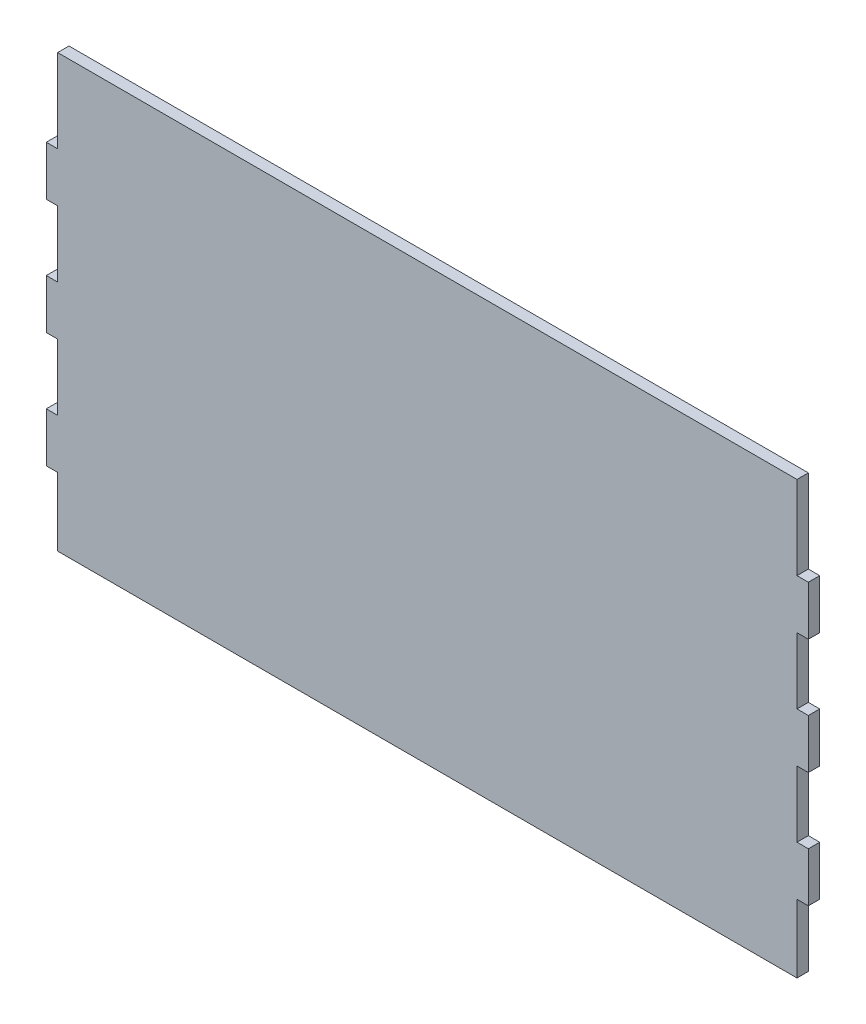
SolidWorks part; units mm, degrees
ref_plane "Front Plane" through (0, 0, 0) normal (0, 0, 1) x (1, 0, 0)
ref_plane "Top Plane" through (0, 0, 0) normal (0, 1, 0) x (1, 0, 0)
ref_plane "Right Plane" through (0, 0, 0) normal (1, 0, 0) x (0, 0, -1)
sketch "Croquis1" plane through (0, 0, 0) normal (0, 0, 1) x (1, 0, 0)
  line L1 (-100.6, 55) -> (100.6, 55)
  line L2 (-100.6, 55) -> (-100.6, -55)
  line L3 (-100.6, -55) -> (100.6, -55)
  line L4 (100.6, 55) -> (100.6, -55)
  line L5 (-100.6, 55) -> (100.6, -55) construction
  line L6 (-100.6, -55) -> (100.6, 55) construction
  point P0 (0, 0)
  dimension "D1" = 201.2
  dimension "D2" = 110
extrude "Saliente-Extruir1" add sketch "Croquis1" along normal blind 3
sketch "Croquis2" plane through (0, 0, 3) normal (0, 0, 1) x (1, 0, 0)
  line L0 (-100.6, 55) -> (-100.6, -55) construction
  line L1 (-100.6, 37) -> (-97.6, 37)
  line L2 (-100.6, 37) -> (-100.6, 23.9518)
  line L3 (-100.6, 23.9518) -> (-97.6, 23.9518)
  line L6 (-100.6, 6.5241) -> (-100.6, -6.5241)
  line L8 (-100.6, 6.5241) -> (-97.6, 6.5241)
  line L10 (-100.6, -6.5241) -> (-97.6, -6.5241)
  line L11 (-100.6, -23.9518) -> (-100.6, -37)
  line L12 (-100.6, -23.9518) -> (-97.6, -23.9518)
  line L14 (-100.6, -37) -> (-97.6, -37)
  line L15 (-100.6, -55) -> (100.6, -55) construction
  line L16 (100.6, 55) -> (-100.6, 55) construction
  line L17 (0, -55) -> (0, 55) construction
  line L18 (100.6, -23.9518) -> (97.6, -23.9518)
  line L19 (-97.6, -52) -> (97.6, -52)
  line L20 (97.6, -52) -> (97.6, 52)
  line L21 (-97.6, 52) -> (-97.6, -52)
  line L22 (97.6, 52) -> (-97.6, 52)
  line L24 (97.6, -52) -> (97.6, -37)
  line L25 (-97.6, 52) -> (-97.6, 37)
  line L28 (100.6, -37) -> (97.6, -37)
  line L29 (100.6, -23.9518) -> (100.6, -37)
  line L30 (100.6, 6.5241) -> (97.6, 6.5241)
  line L32 (100.6, -6.5241) -> (97.6, -6.5241)
  line L33 (100.6, 6.5241) -> (100.6, -6.5241)
  line L34 (100.6, 23.9518) -> (97.6, 23.9518)
  line L36 (100.6, 37) -> (97.6, 37)
  line L37 (100.6, 37) -> (100.6, 23.9518)
  line L38 (-97.6, 23.9518) -> (-97.6, 6.5241)
  line L39 (-97.6, -6.5241) -> (-97.6, -23.9518)
  line L40 (-97.6, -37) -> (-97.6, -52)
  line L41 (97.6, -23.9518) -> (97.6, -6.5241)
  line L42 (97.6, 6.5241) -> (97.6, 23.9518)
  line L43 (97.6, 37) -> (97.6, 52)
  line L44 (-97.6, 52) -> (-97.6, 55)
  line L45 (97.6, 52) -> (97.6, 55)
  line L46 (-97.6, -52) -> (-97.6, -55)
  line L47 (97.6, -52) -> (97.6, -55)
  line L48 (-97.6, -55) -> (97.6, -55)
  line L49 (-97.6, 55) -> (97.6, 55)
  line M3 (100.6, -55) -> (100.6, 55)
  line M4 (100.6, 55) -> (-100.6, 55)
  line M5 (-100.6, 55) -> (-100.6, -55)
  line M6 (-100.6, -55) -> (100.6, -55)
  dimension "D3" = 18
  dimension "D4" = 18
  dimension "D1" = 3
  dimension "D2" = 3
extrude "Cortar-Extruir1" cut sketch "Croquis2" against normal blind 3 contours L25 L44 L1 M4 M5 | L38 L3 L8 M5 | L45 L43 L36 M3 M4 | L42 L30 L34 M3 | L41 L18 L32 M3 | L24 L47 L28 M6 M3 | L39 L10 L12 M5 | L46 L40 L14 M5 M6
sketch "Croquis4" plane through (0, 0, 0) normal (0, 0, -1) x (-1, 0, 0)
  line L6 (97.6, 55) -> (97.6, 37) construction
  line L7 (-97.6, 55) -> (97.6, 55)
  line L8 (-97.6, 55) -> (-97.6, 59)
  line L9 (-97.6, 59) -> (97.6, 59)
  line L10 (97.6, 55) -> (97.6, 59)
  dimension "D1" = 4
extrude "Saliente-Extruir3" add sketch "Croquis4" against normal blind 3
sketch "Croquis6" plane through (0, 0, 0) normal (0, 0, -1) x (-1, 0, 0)
  line L0 (-175, -10.7078) -> (175, -10.7078) construction
  text T0 "ITAM " font "Century Gothic" height 25
  point P2 (0, -10.7078)
  dimension "D1" = 350
extrude "Cortar-Extruir4" cut sketch "Croquis6" against normal blind 1.5
